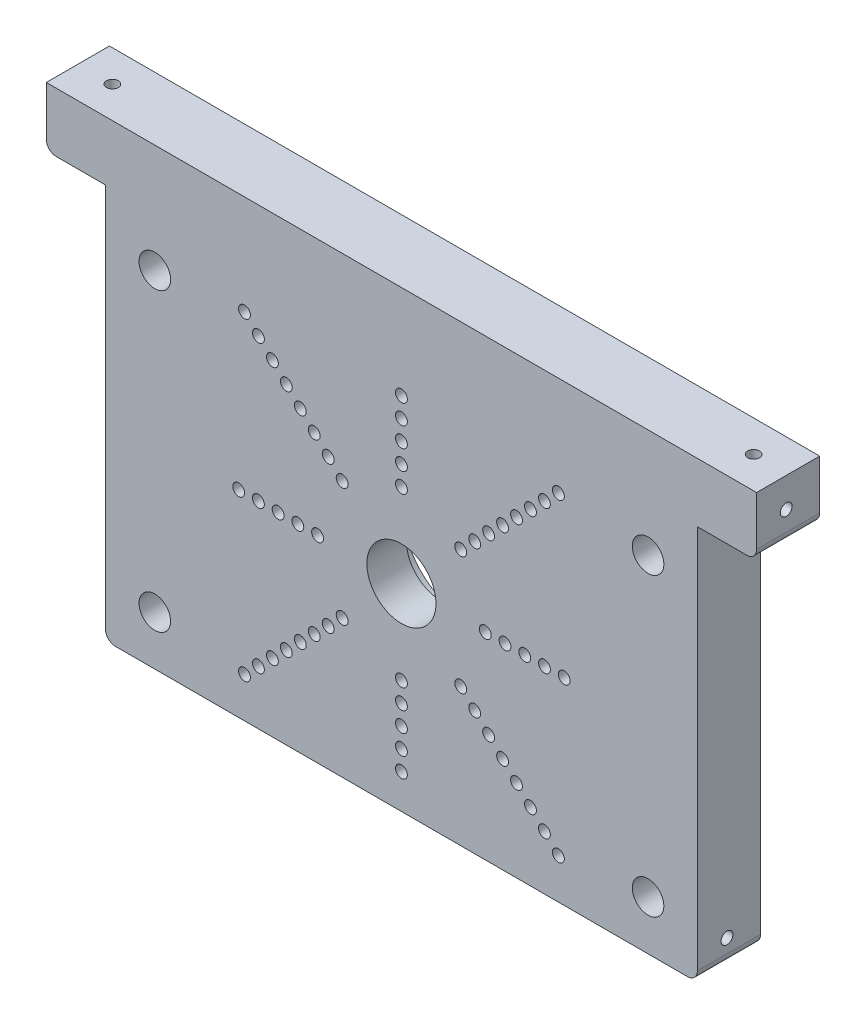
SolidWorks part; units mm, degrees
ref_plane "Front Plane" through (0, 0, 0) normal (0, 0, 1) x (1, 0, 0)
ref_plane "Top Plane" through (0, 0, 0) normal (0, 1, 0) x (1, 0, 0)
ref_plane "Right Plane" through (0, 0, 0) normal (1, 0, 0) x (0, 0, -1)
sketch "Sketch1" plane through (0, 0, 0) normal (0, 0, 1) x (1, 0, 0)
  line L1 (150, 100) -> (-150, 100)
  line L2 (150, 100) -> (150, -100)
  line L3 (150, -100) -> (-150, -100)
  line L4 (-150, 100) -> (-150, -100)
  circle A0 centre (125, 75) radius 8
  circle A1 centre (125, -75) radius 8
  circle A2 centre (-125, -75) radius 8
  circle A3 centre (-125, 75) radius 8
  point P0 (0, 0)
  dimension "D7" = 16
  dimension "D8" = 16
  dimension "D9" = 16
  dimension "D10" = 16
  dimension "D1" = 200
  dimension "D2" = 300
extrude "Boss-Extrude1" add sketch "Sketch1" along normal blind 32
sketch "Sketch2" plane through (0, 0, 32) normal (0, 0, 1) x (1, 0, 0)
  line L7 (-150, -100) -> (-150, 100) construction
  circle A2 centre (58.3363, -58.3363) radius 3
  circle A3 centre (51.2652, -51.2652) radius 3
  circle A4 centre (44.1942, -44.1942) radius 3
  circle A5 centre (37.1231, -37.1231) radius 3
  circle A6 centre (30.052, -30.052) radius 3
  circle A8 centre (-65.4074, 65.4074) radius 3
  circle A9 centre (-72.4784, 72.4784) radius 3
  circle A10 centre (42.5, 0) radius 3
  circle A11 centre (52.5, 0) radius 3
  circle A12 centre (62.5, 0) radius 3
  circle A13 centre (72.5, 0) radius 3
  circle A14 centre (82.5, 0) radius 3
  circle A15 centre (-79.5495, 79.5495) radius 3
  circle A18 centre (0, -82.5) radius 3
  circle A19 centre (0, -72.5) radius 3
  circle A20 centre (0, -62.5) radius 3
  circle A21 centre (0, -52.5) radius 3
  circle A22 centre (0, -42.5) radius 3
  circle A24 centre (65.4074, 65.4074) radius 3
  circle A25 centre (72.4784, 72.4784) radius 3
  circle A26 centre (-58.3363, -58.3363) radius 3
  circle A27 centre (-51.2652, -51.2652) radius 3
  circle A28 centre (-44.1942, -44.1942) radius 3
  circle A29 centre (-37.1231, -37.1231) radius 3
  circle A30 centre (-30.052, -30.052) radius 3
  circle A31 centre (79.5495, 79.5495) radius 3
  circle A34 centre (-82.5, 0) radius 3
  circle A35 centre (-72.5, 0) radius 3
  circle A36 centre (-62.5, 0) radius 3
  circle A37 centre (-52.5, 0) radius 3
  circle A38 centre (-42.5, 0) radius 3
  circle A40 centre (65.4074, -65.4074) radius 3
  circle A41 centre (72.4784, -72.4784) radius 3
  circle A42 centre (-58.3363, 58.3363) radius 3
  circle A43 centre (-51.2652, 51.2652) radius 3
  circle A44 centre (-44.1942, 44.1942) radius 3
  circle A45 centre (-37.1231, 37.1231) radius 3
  circle A46 centre (-30.052, 30.052) radius 3
  circle A47 centre (79.5495, -79.5495) radius 3
  circle A50 centre (0, 82.5) radius 3
  circle A51 centre (0, 72.5) radius 3
  circle A52 centre (0, 62.5) radius 3
  circle A53 centre (0, 52.5) radius 3
  circle A54 centre (0, 42.5) radius 3
  circle A56 centre (-65.4074, -65.4074) radius 3
  circle A57 centre (-72.4784, -72.4784) radius 3
  circle A58 centre (58.3363, 58.3363) radius 3
  circle A59 centre (51.2652, 51.2652) radius 3
  circle A60 centre (44.1942, 44.1942) radius 3
  circle A61 centre (37.1231, 37.1231) radius 3
  circle A62 centre (30.052, 30.052) radius 3
  circle A63 centre (-79.5495, -79.5495) radius 3
  point P128 (0, 0)
  point P138 (0, 0)
  dimension "D2" = 8
extrude "Cut-Extrude2" cut sketch "Sketch2" against normal blind 32
sketch "Sketch4" plane through (0, 0, 0) normal (0, 0, -1) x (-1, 0, 0)
  line L0 (0, 100) -> (0, 80) construction
  line L1 (-150, 100) -> (150, 100) construction
  line L2 (150, 0) -> (150, 7.5) construction
  line L3 (-7.5, -18.1066) -> (-7.5, -83.9696)
  line L4 (150, 7.5) -> (150, -7.5) construction
  line L7 (0, 100) -> (0, 80) construction
  line L8 (0, -100) -> (0, -80) construction
  line L9 (150, 100) -> (150, -100) construction
  line L11 (150, -100) -> (-150, -100) construction
  line L12 (139.6966, 7.5) -> (18.1066, 7.5)
  line L14 (-139.6966, -7.5) -> (-18.1066, -7.5)
  line L15 (150, -7.5) -> (150, 7.5)
  line L16 (-91.9422, 81.3356) -> (-18.1066, 7.5)
  line L17 (-7.5, 83.9696) -> (-7.5, 18.1066)
  line L18 (77.2382, 87.8448) -> (7.5, 18.1066)
  line L19 (139.6966, 7.5) -> (18.1066, 7.5)
  line L20 (91.9422, -81.3356) -> (18.1066, -7.5)
  line L21 (7.5, -83.9696) -> (7.5, -18.1066)
  line L22 (-77.2382, -87.8448) -> (-7.5, -18.1066)
  line L23 (-18.1066, -7.5) -> (-91.9422, -81.3356)
  line L25 (-18.1066, 7.5) -> (-139.6966, 7.5)
  line L26 (-18.1066, 7.5) -> (-139.6966, 7.5)
  line L28 (-7.5, 18.1066) -> (-77.2382, 87.8448)
  line L30 (7.5, 18.1066) -> (7.5, 83.9696)
  line L33 (18.1066, 7.5) -> (91.9422, 81.3356)
  line L35 (18.1066, -7.5) -> (139.6966, -7.5)
  line L37 (7.5, -18.1066) -> (77.2382, -87.8448)
  arc A0 (0, 80) -> (0, -80) centre (47.1429, 0) cw
  arc A1 (0, 80) -> (0, -80) centre (-47.1429, 0) ccw
  point P40 (0, 0)
  dimension "D5" = 15
  dimension "D1" = 20
  dimension "D4" = 20
  dimension "D6" = 8
extrude "Cut-Extrude4" cut sketch "Sketch4" against normal blind 16 contours L16 A1 L25 | L17 A1 L28 | A0 L30 L18 | A0 L33 L12 | A0 L35 L20 | A0 L37 L21 | L22 A1 L3 | L14 A1 L23
fillet "Fillet4" radius 10 8 edges at (-18.1066, 7.5, 8) (-7.5, 18.1066, 8) (7.5, 18.1066, 8) (18.1066, 7.5, 8) (18.1066, -7.5, 8) (7.5, -18.1066, 8) (-7.5, -18.1066, 8) (-18.1066, -7.5, 8)
fillet "Fillet8" radius 10 16 edges at (-91.9422, -81.3356, 8) (-139.6966, -7.5, 8) (-139.6966, 7.5, 8) (-91.9422, 81.3356, 8) (-77.2382, 87.8448, 8) (7.5, 83.9696, 8) (-7.5, 83.9696, 8) (77.2382, 87.8448, 8) (91.9422, 81.3356, 8) (139.6966, -7.5, 8) (139.6966, 7.5, 8) (91.9422, -81.3356, 8) (77.2382, -87.8448, 8) (7.5, -83.9696, 8) (-7.5, -83.9696, 8) (-77.2382, -87.8448, 8)
sketch "Sketch5" plane through (0, 0, 0) normal (0, 0, -1) x (-1, 0, 0)
  line L0 (-150, 100) -> (-180, 100)
  line L1 (-180, 100) -> (-180, 130)
  line L2 (-180, 130) -> (180, 130)
  line L3 (180, 130) -> (180, 100)
  line L4 (180, 100) -> (150, 100)
  line L5 (-150, 100) -> (150, 100) construction
  line L6 (-150, 100) -> (150, 100)
  dimension "D1" = 30
  dimension "D2" = 30
extrude "Boss-Extrude2" add sketch "Sketch5" against normal blind 32
sketch "Sketch6" plane through (0, 0, 0) normal (0, 0, -1) x (-1, 0, 0)
  line L0 (150, -100) -> (-150, 100) construction
  circle A0 centre (0, 0) radius 31
  dimension "D1" = 62
extrude "Cut-Extrude5" cut sketch "Sketch6" against normal blind 12
sketch "Sketch7" plane through (0, 0, 12) normal (0, 0, -1) x (-1, 0, 0)
  circle A0 centre (0, 0) radius 17.5
  dimension "D1" = 35
extrude "Cut-Extrude6" cut sketch "Sketch7" against normal blind 106
fillet "Fillet9" radius 5 4 edges at (-180, 100, 16) (-150, -100, 16) (180, 100, 16) (150, -100, 16)
sketch "Sketch8" plane through (180, 0, 0) normal (1, 0, 0) x (0, 0, -1)
  line L1 (-32, 130) -> (0, 130)
  line L2 (-32, 130) -> (-32, 100)
  circle A0 centre (-17, 115) radius 3
  dimension "D1" = 6
  dimension "D2" = 15
extrude "Cut-Extrude7" cut sketch "Sketch8" against normal blind 10 contours A0
sketch "Sketch9" plane through (-180, 0, 0) normal (-1, 0, 0) x (0, 0, 1)
  circle A0 centre (17, 115) radius 3
  dimension "D3" = 6
extrude "Cut-Extrude8" cut sketch "Sketch9" against normal blind 10
sketch "Sketch10" plane through (-150, 0, 0) normal (-1, 0, 0) x (0, 0, 1)
  line L0 (32, 100) -> (32, -95) construction
  line L1 (0, -100) -> (15, -100)
  circle A0 centre (17, -88) radius 3
  dimension "D3" = 6
  dimension "D1" = 15
extrude "Cut-Extrude9" cut sketch "Sketch10" against normal blind 10 contours A0
sketch "Sketch11" plane through (150, 0, 0) normal (1, 0, 0) x (0, 0, -1)
  line L1 (-32, -88) -> (-17, -88)
  line L2 (-32, -100) -> (-32, -88)
  circle A0 centre (-17, -88) radius 3
  dimension "D3" = 6
  dimension "D1" = 12
  dimension "D2" = 15
extrude "Cut-Extrude10" cut sketch "Sketch11" against normal blind 10
sketch "Sketch12" plane through (0, 100, 0) normal (0, -1, 0) x (-1, 0, 0)
  line L0 (-160.6531, -13.6359) -> (-162.5, -16) construction
  line L5 (-164.3469, -13.6359) -> (-162.5, -16) construction
  line L6 (160.6531, -13.6359) -> (164.3469, -18.3641) construction
  line L9 (150, -32) -> (175, -32)
  circle A0 centre (-162.5, -16) radius 3
  circle A1 centre (162.5, -16) radius 3
  dimension "D1" = 6
  dimension "D2" = 6
extrude "Cut-Extrude11" cut sketch "Sketch12" against normal blind 90 contours A1 | A0
sketch "Sketch13" plane through (0, -100, 0) normal (0, -1, 0) x (-1, 0, 0)
  line L0 (145, -32) -> (-145, -32) construction
  line L1 (150, -32) -> (150, 0) construction
  line L5 (141, -17) -> (138, -17) construction
  circle A0 centre (138, -17) radius 3
  dimension "D2" = 6
  dimension "D1" = 12
  dimension "D3" = 15
extrude "Cut-Extrude12" cut sketch "Sketch13" against normal blind 5
sketch "Sketch14" plane through (0, -100, 0) normal (0, -1, 0) x (-1, 0, 0)
  circle A0 centre (-138, -17) radius 3
  dimension "D3" = 6
extrude "Cut-Extrude13" cut sketch "Sketch14" against normal blind 5
